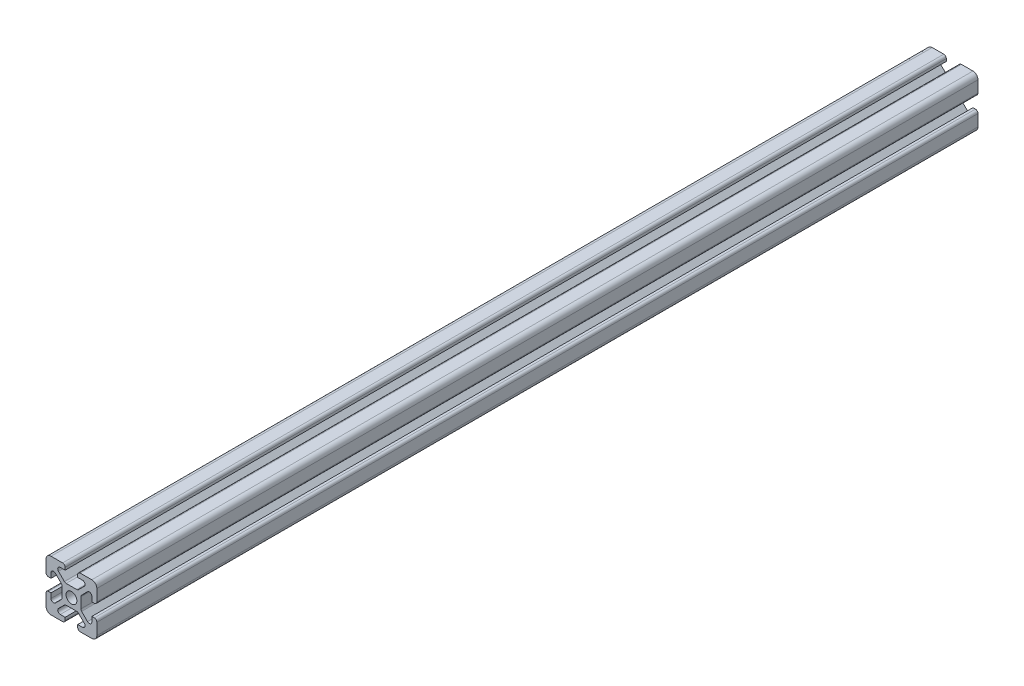
SolidWorks part; units mm, degrees
ref_plane "Front Plane" through (0, 0, 0) normal (0, 0, 1) x (1, 0, 0)
ref_plane "Top Plane" through (0, 0, 0) normal (0, 1, 0) x (1, 0, 0)
ref_plane "Right Plane" through (0, 0, 0) normal (1, 0, 0) x (0, 0, -1)
sketch "Sketch1" plane through (0, 0, 0) normal (0, 0, 1) x (1, 0, 0)
  line L0 (10.1, 10) -> (10.1, 0.1) construction
  line L1 (2, 0) -> (6.6, 0)
  line L2 (0, 2) -> (0, 6.6)
  line L3 (2, 20.2) -> (6.6, 20.2)
  line L4 (20.2, 2) -> (20.2, 6.6)
  line L5 (10.1, 10) -> (0, 10) construction
  line L6 (7.6, 19.2) -> (7.6, 18.2)
  line L7 (7.6, 18.2) -> (5.6642, 18.2)
  line L8 (4.9571, 16.4929) -> (7.3071, 14.1429)
  line L9 (8.0142, 13.85) -> (12.1858, 13.85)
  line L10 (12.8929, 14.1429) -> (15.2429, 16.4929)
  line L11 (14.5358, 18.2) -> (12.6, 18.2)
  line L12 (12.6, 18.2) -> (12.6, 19.2)
  line L13 (-250.157, -110.88) -> (53.1764, -110.88) construction
  line L14 (13.6, 20.2) -> (18.2, 20.2)
  line L15 (19.2, 12.6) -> (18.2, 12.6)
  line L16 (18.2, 12.6) -> (18.2, 14.5358)
  line L17 (16.4929, 15.2429) -> (14.1429, 12.8929)
  line L18 (13.85, 12.1858) -> (13.85, 8.0142)
  line L19 (14.1429, 7.3071) -> (16.4929, 4.9571)
  line L20 (18.2, 5.6642) -> (18.2, 7.6)
  line L21 (18.2, 7.6) -> (19.2, 7.6)
  line L22 (12.6, 1) -> (12.6, 2)
  line L23 (12.6, 2) -> (14.5358, 2)
  line L24 (15.2429, 3.7071) -> (12.8929, 6.0571)
  line L25 (12.1858, 6.35) -> (8.0142, 6.35)
  line L26 (7.3071, 6.0571) -> (4.9571, 3.7071)
  line L27 (5.6642, 2) -> (7.6, 2)
  line L28 (7.6, 2) -> (7.6, 1)
  line L29 (1, 7.6) -> (2, 7.6)
  line L30 (2, 7.6) -> (2, 5.6642)
  line L31 (3.7071, 4.9571) -> (6.0571, 7.3071)
  line L32 (6.35, 8.0142) -> (6.35, 12.1858)
  line L33 (6.0571, 12.8929) -> (3.7071, 15.2429)
  line L34 (2, 14.5358) -> (2, 12.6)
  line L35 (2, 12.6) -> (1, 12.6)
  line L36 (20.2, 13.6) -> (20.2, 18.2)
  line L37 (13.6, 0) -> (18.2, 0)
  line L38 (0, 13.6) -> (0, 18.2)
  circle A0 centre (10.1, 10) radius 2.15
  arc A1 (12.8929, 14.1429) -> (12.1858, 13.85) centre (12.1858, 14.85) cw
  arc A2 (8.0142, 13.85) -> (7.3071, 14.1429) centre (8.0142, 14.85) cw
  arc A3 (15.2429, 16.4929) -> (14.5358, 18.2) centre (14.5358, 17.2) ccw
  arc A4 (5.6642, 18.2) -> (4.9571, 16.4929) centre (5.6642, 17.2) ccw
  arc A5 (2, 0) -> (0, 2) centre (2, 2) cw
  arc A6 (18.2, 0) -> (20.2, 2) centre (18.2, 2) ccw
  arc A7 (20.2, 18.2) -> (18.2, 20.2) centre (18.2, 18.2) ccw
  arc A8 (2, 20.2) -> (0, 18.2) centre (2, 18.2) ccw
  arc A9 (18.2, 14.5358) -> (16.4929, 15.2429) centre (17.2, 14.5358) ccw
  arc A10 (13.85, 12.1858) -> (14.1429, 12.8929) centre (14.85, 12.1858) cw
  arc A11 (14.1429, 7.3071) -> (13.85, 8.0142) centre (14.85, 8.0142) cw
  arc A12 (16.4929, 4.9571) -> (18.2, 5.6642) centre (17.2, 5.6642) ccw
  arc A13 (14.5358, 2) -> (15.2429, 3.7071) centre (14.5358, 3) ccw
  arc A14 (12.1858, 6.35) -> (12.8929, 6.0571) centre (12.1858, 5.35) cw
  arc A15 (7.3071, 6.0571) -> (8.0142, 6.35) centre (8.0142, 5.35) cw
  arc A16 (4.9571, 3.7071) -> (5.6642, 2) centre (5.6642, 3) ccw
  arc A17 (2, 5.6642) -> (3.7071, 4.9571) centre (3, 5.6642) ccw
  arc A18 (6.35, 8.0142) -> (6.0571, 7.3071) centre (5.35, 8.0142) cw
  arc A19 (6.0571, 12.8929) -> (6.35, 12.1858) centre (5.35, 12.1858) cw
  arc A20 (3.7071, 15.2429) -> (2, 14.5358) centre (3, 14.5358) ccw
  arc A21 (20.2, 13.6) -> (19.2, 12.6) centre (19.2, 13.6) cw
  arc A22 (20.2, 6.6) -> (19.2, 7.6) centre (19.2, 6.6) ccw
  arc A23 (13.6, 0) -> (12.6, 1) centre (13.6, 1) cw
  arc A24 (7.6, 1) -> (6.6, 0) centre (6.6, 1) cw
  arc A25 (1, 7.6) -> (0, 6.6) centre (1, 6.6) ccw
  arc A26 (1, 12.6) -> (0, 13.6) centre (1, 13.6) cw
  arc A27 (7.6, 19.2) -> (6.6, 20.2) centre (6.6, 19.2) ccw
  arc A28 (13.6, 20.2) -> (12.6, 19.2) centre (13.6, 19.2) ccw
  point P21 (12.6, 13.85)
  point P24 (7.6, 13.85)
  point P31 (0, 0)
  point P36 (20.2, 20.2)
  point P39 (0, 20.2)
  point P91 (10.1, 10.1)
  point P105 (12.6, 20.2)
  dimension "D3" = 4.3
  dimension "D9" = 1
  dimension "D10" = 2
  dimension "D13" = 1
  dimension "D1" = 20.2
  dimension "D2" = 10.1
  dimension "D4" = 5
  dimension "D5" = 2.5
  dimension "D6" = 6.35
  dimension "D7" = 2
  dimension "D8" = 45
  dimension "D12" = 10
  dimension "D14" = 20.2
  dimension "D15" = 7.6
  dimension "D16" = 6.35
  dimension "D11" = 4
extrude "Boss-Extrude1" add sketch "Sketch1" along normal blind 350
